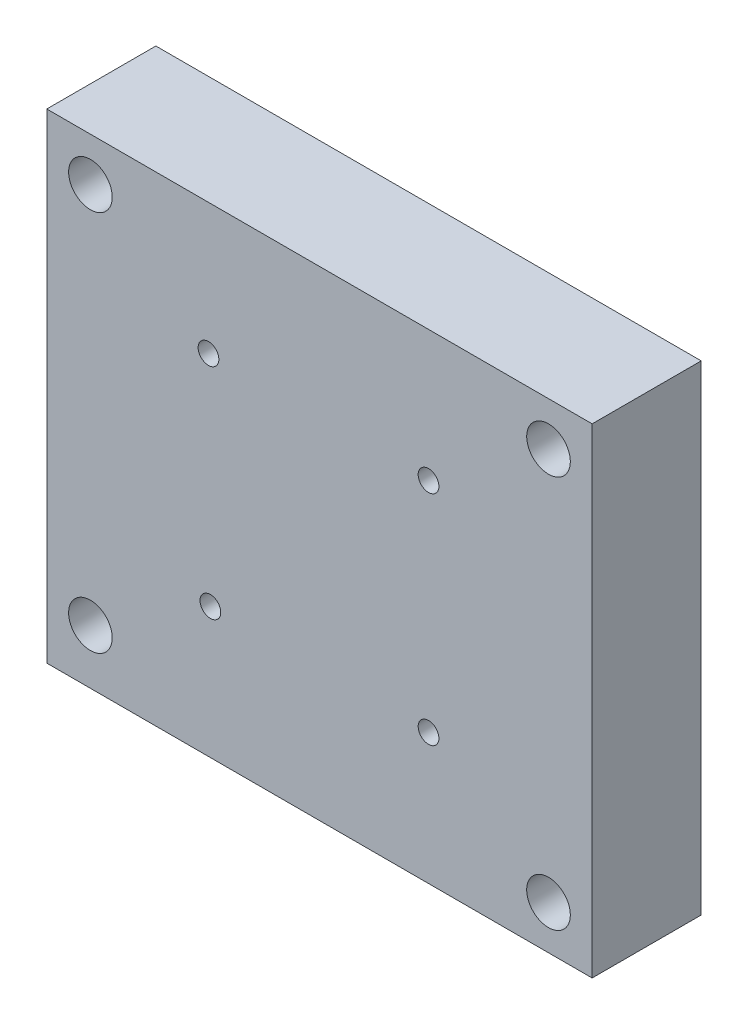
SolidWorks part; units mm, degrees
material "Custom Plastic"
ref_plane "Front Plane" through (0, 0, 0) normal (0, 0, 1) x (1, 0, 0)
ref_plane "Top Plane" through (0, 0, 0) normal (0, 1, 0) x (1, 0, 0)
ref_plane "Right Plane" through (0, 0, 0) normal (1, 0, 0) x (0, 0, -1)
sketch "Sketch2" plane through (0, 0, 0) normal (1, 0, 0) x (0, 0, -1)
  line L0 (0, -6) -> (5, -6)
  line L1 (0, -6) -> (0, 16)
  line L2 (0, 16) -> (5, 16)
  line L3 (5, 16) -> (5, -6)
  dimension "D1" = 5
  dimension "D2" = 22
extrude "Boss-Extrude1" add sketch "Sketch2" along normal blind 25
hole_wizard "Tap Drill for M2.5x0.45 Tap1" positions "Sketch5" profile "Sketch4" hole size "M2.5x0.45" standard "ANSI Metric"
sketch "Sketch5" plane through (0, -6, 0) normal (0, -1, 0) x (-1, 0, 0)
  line L1 (-25, 5) -> (0, 5) construction
  line L2 (-12.5, 5) -> (-12.5, 0) construction
  point P0 (-19.5, 2.5)
  point P2 (-12.5, 2.5)
  point P4 (-5.5, 2.5)
  dimension "D1" = 7
  dimension "D2" = 7
  dimension "D4" = 2.5
  dimension "D5" = 2.5
  dimension "D6" = 2.5
sketch "Sketch4" plane through (19.5, -6, -2.5) normal (1, 0, 0) x (0, 0, -1)
  line L0 (0, 0) -> (0, 5)
  line L1 (0, 5) -> (1.25, 5)
  line L2 (1.25, 5) -> (1.25, 0)
  line L5 (1.25, 0) -> (0, 0)
  line L10 (0, 5) -> (-1.25, 5) construction
  line L11 (0, -6.35) -> (0, 107.95) construction
  dimension "Hole Dia." = 2.5
  dimension "Hole Depth" = 5
  dimension "Drill Angle" = 180
hole_wizard "Tap Drill for M1.2x0.25 Tap1" positions "Sketch7" profile "Sketch6" hole size "M1.2x0.25" standard "ANSI Metric" end condition through all
sketch "Sketch7" plane through (0, 0, -5) normal (0, 0, -1) x (-1, 0, 0)
  line L0 (-12.5, -6) -> (-12.5, 16) construction
  line L1 (-25, -6) -> (0, -6) construction
  line L2 (-25, 16) -> (0, 16) construction
  line L4 (-25, 5) -> (0, 5) construction
  line L5 (-25, -6) -> (-25, 16) construction
  line L6 (0, -6) -> (0, 16) construction
  point P0 (-17.5, 10)
  point P3 (-7.4131, 10)
  point P5 (-17.5, 0)
  point P8 (-7.5, 0)
  dimension "D1" = 10.0869
  dimension "D2" = 10
  dimension "D3" = 10
  dimension "D4" = 10
  dimension "D5" = 5
  dimension "D6" = 5
sketch "Sketch6" plane through (17.5, 10, -5) normal (1, 0, 0) x (0, 1, 0)
  line L0 (0, 0) -> (0, 5)
  line L1 (0, 5) -> (0.475, 5)
  line L2 (0.475, 5) -> (0.475, 0)
  line L5 (0.475, 0) -> (0, 0)
  line L11 (0, -6.35) -> (0, 107.95) construction
  dimension "Thru Hole Dia." = 0.95
  dimension "Thru Hole Depth" = 5
hole_wizard "Tap Drill for M2x0.4 Tap1" positions "Sketch11" profile "Sketch10" hole size "M2x0.4" standard "ANSI Metric" end condition through all
sketch "Sketch11" plane through (0, 0, 0) normal (0, 0, 1) x (1, 0, 0)
  point P0 (2, 14)
  point P3 (2, -3.5)
  point P6 (23, -4)
  point P9 (23, 14)
sketch "Sketch10" plane through (2, 14, 0) normal (1, 0, 0) x (0, -1, 0)
  line L0 (0, 0) -> (0, 5)
  line L1 (0, 5) -> (1, 5)
  line L2 (1, 5) -> (1, 0)
  line L5 (1, 0) -> (0, 0)
  line L11 (0, -6.35) -> (0, 107.95) construction
  dimension "Thru Hole Dia." = 2
  dimension "Thru Hole Depth" = 5
